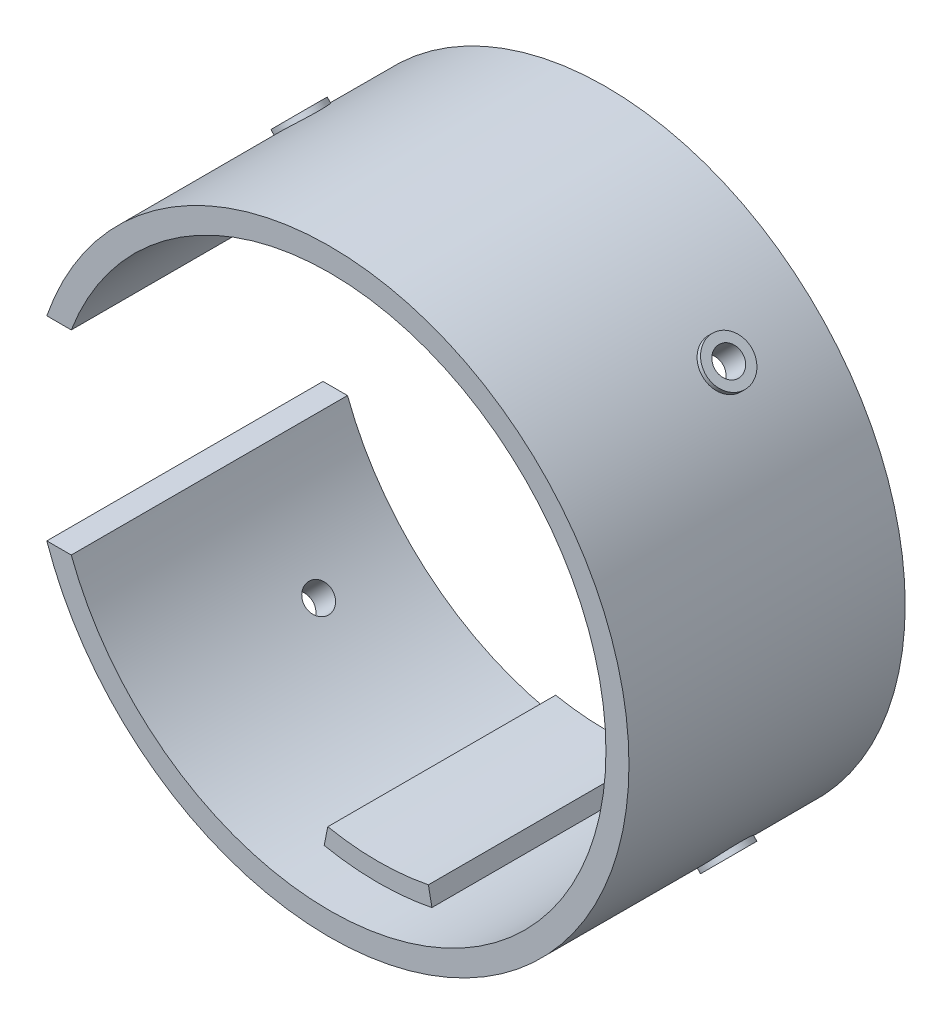
SolidWorks part; units mm, degrees
ref_plane "Front Plane" through (0, 0, 0) normal (0, 0, 1) x (1, 0, 0)
ref_plane "Top Plane" through (0, 0, 0) normal (0, 1, 0) x (1, 0, 0)
ref_plane "Right Plane" through (0, 0, 0) normal (1, 0, 0) x (0, 0, -1)
sketch "Sketch1" plane through (0, 0, 0) normal (0, 0, 1) x (1, 0, 0)
  line L0 (0, 0) -> (-33.6855, 0) construction
  line L1 (-33.6855, -12.7) -> (-33.6855, 12.7) construction
  line L2 (-33.6855, 12.7) -> (-36.8742, 12.7)
  line L3 (-33.6855, -12.7) -> (-36.8742, -12.7)
  arc A0 (-33.6855, -12.7) -> (-33.6855, 12.7) centre (0, 0) ccw
  arc A1 (-36.8742, -12.7) -> (-36.8742, 12.7) centre (0, 0) ccw
  point P8 (-33.6855, 0)
  dimension "D1" = 72
  dimension "D2" = 3
  dimension "D3" = 25.4
extrude "Boss-Extrude1" add sketch "Sketch1" along normal blind 36
sketch "Sketch2" plane through (0, 0, 0) normal (0, 0, -1) x (-1, 0, 0)
  line L0 (0, 0) -> (0, 36) construction
  line L5 (0, 0) -> (-39, 0) construction
  line L10 (0, 0) -> (-7.0233, 35.3083) construction
  line L11 (0, 0) -> (7.0233, 35.3083) construction
  line L12 (-7.0233, 35.3083) -> (-6.555, 32.9544)
  line L13 (7.0233, 35.3083) -> (6.555, 32.9544)
  line L14 (7.0233, -35.3083) -> (6.555, -32.9544)
  line L15 (-7.0233, -35.3083) -> (-6.555, -32.9544)
  arc A0 (33.6855, 12.7) -> (33.6855, -12.7) centre (0, 0) ccw construction
  arc A1 (36.8742, 12.7) -> (36.8742, -12.7) centre (0, 0) ccw construction
  arc A2 (-7.0233, 35.3083) -> (7.0233, 35.3083) centre (0, 0) cw
  arc A4 (-6.555, 32.9544) -> (6.555, 32.9544) centre (0, 0) cw
  circle A5 centre (0, 0) radius 33.6 construction
  arc A6 (-6.555, -32.9544) -> (6.555, -32.9544) centre (0, 0) ccw
  arc A7 (-7.0233, -35.3083) -> (7.0233, -35.3083) centre (0, 0) ccw
  dimension "D1" = 22.5
extrude "Boss-Extrude2" add sketch "Sketch2" against normal blind 29.7 separate body
ref_plane "Plane1" through (-23.1927, 23.1927, 0) normal (0.7071, -0.7071, 0) x (0, 0, -1)
ref_plane "Plane2" through (-26.7283, 26.7283, 0) normal (0.7071, -0.7071, 0) x (0, 0, -1)
sketch "Sketch3" plane through (-26.7283, 26.7283, 0) normal (0.7071, -0.7071, 0) x (0, 0, -1)
  line L0 (0, 0) -> (-36, 0) construction
  line L1 (-36, 39) -> (-36, -39) construction
  line L2 (0, -39) -> (0, 39) construction
  circle A0 centre (-12, 0) radius 3
  dimension "D1" = 6
  dimension "D2" = 12
extrude "Boss-Extrude3" add sketch "Sketch3" against normal blind 1.8
sketch "Sketch4" plane through (-28.0011, 28.0011, 0) normal (-0.7071, 0.7071, 0) x (0, 0, 1)
  circle A0 centre (12, 0) radius 1.8
  dimension "D1" = 3.6
extrude "Cut-Extrude1" cut sketch "Sketch4" against normal up to next
pattern_circular "CirPattern1" count 4 every 90 about axis through (0, 0, 0) along (0, 0, 1) of "Boss-Extrude3", "Cut-Extrude1"
